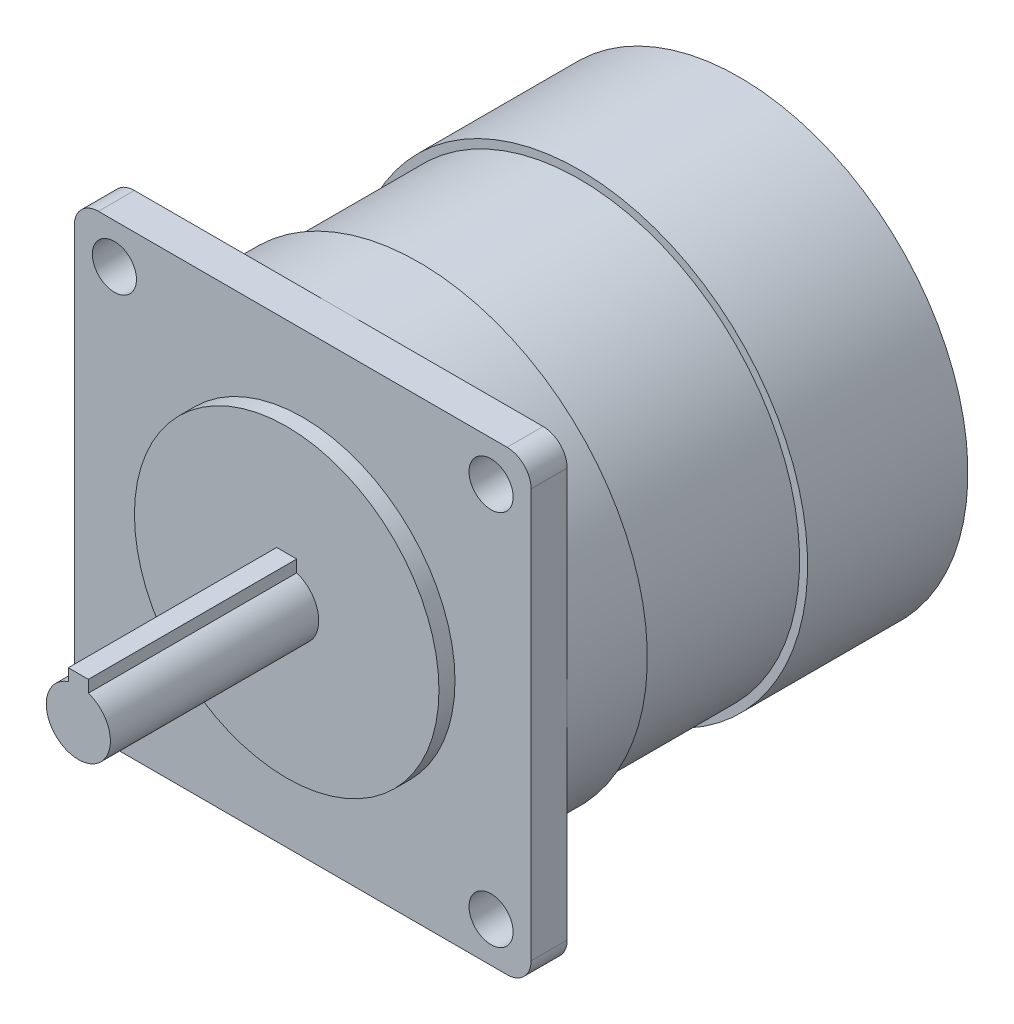
SolidWorks part; units mm, degrees
ref_plane "前视基准面" through (0, 0, 0) normal (0, 0, 1) x (1, 0, 0)
ref_plane "上视基准面" through (0, 0, 0) normal (0, 1, 0) x (1, 0, 0)
ref_plane "右视基准面" through (0, 0, 0) normal (1, 0, 0) x (0, 0, -1)
sketch "草图1" plane through (0, 0, 0) normal (0, 0, 1) x (1, 0, 0)
  line L1 (-28.5, -28.5) -> (28.5, -28.5)
  line L2 (-28.5, -28.5) -> (-28.5, 28.5)
  line L3 (-28.5, 28.5) -> (28.5, 28.5)
  line L4 (28.5, -28.5) -> (28.5, 28.5)
  line L5 (-28.5, -28.5) -> (28.5, 28.5) construction
  line L6 (-28.5, 28.5) -> (28.5, -28.5) construction
  point P0 (0, 0)
  dimension "D1" = 57
  dimension "D2" = 57
extrude "凸台-拉伸1" add sketch "草图1" along normal blind 4.5
fillet "圆角1" radius 3 4 edges at (-28.5, -28.5, 2.25) (28.5, -28.5, 2.25) (28.5, 28.5, 2.25) (-28.5, 28.5, 2.25)
sketch "草图2" plane through (0, 0, 4.5) normal (0, 0, 1) x (1, 0, 0)
  circle A0 centre (0, 0) radius 19
  dimension "D1" = 38
extrude "凸台-拉伸2" add sketch "草图2" along normal blind 2
sketch "草图3" plane through (0, 0, 6.5) normal (0, 0, 1) x (1, 0, 0)
  line L4 (-1.25, 3.7997) -> (-1.25, 5.2997)
  line L5 (-1.25, 5.2997) -> (1.25, 5.2997)
  line L6 (1.25, 5.2997) -> (1.25, 3.7997)
  arc A0 (-1.25, 3.7997) -> (1.25, 3.7997) centre (0, 0) ccw
  dimension "D1" = 8
  dimension "D4" = 1.5
extrude "凸台-拉伸3" add sketch "草图3" along normal blind 26
sketch "草图4" plane through (0, 0, 4.5) normal (0, 0, 1) x (1, 0, 0)
  line L6 (-23.5, 23.5) -> (-21.5555, 21.5555) construction
  circle A0 centre (-23.5, 23.5) radius 2.75
  circle A1 centre (23.5, 23.5) radius 2.75
  circle A2 centre (-23.5, -23.5) radius 2.75
  circle A3 centre (23.5, -23.5) radius 2.75
  point P0 (0, 0)
  dimension "D3" = 5.5
  dimension "D4" = 5.5
  dimension "D5" = 5.5
  dimension "D6" = 5.5
  dimension "D1" = 47
  dimension "D2" = 47
extrude "切除-拉伸1" cut sketch "草图4" against normal blind 15
sketch "草图5" plane through (0, 0, 0) normal (0, 0, -1) x (-1, 0, 0)
  circle A0 centre (0, 0) radius 28.5
extrude "凸台-拉伸4" add sketch "草图5" along normal blind 10
sketch "草图6" plane through (0, 0, -10) normal (0, 0, -1) x (-1, 0, 0)
  circle A0 centre (0, 0) radius 27.5
  dimension "D1" = 55
extrude "凸台-拉伸5" add sketch "草图6" along normal blind 20
sketch "草图7" plane through (0, 0, -30) normal (0, 0, -1) x (-1, 0, 0)
  circle A0 centre (0, 0) radius 28.5
extrude "凸台-拉伸6" add sketch "草图7" along normal blind 20
